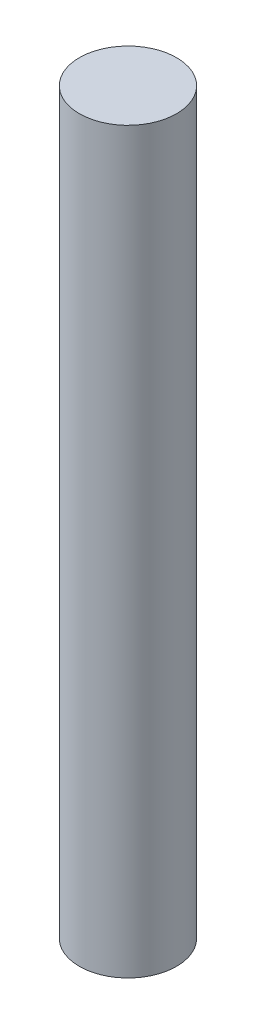
SolidWorks part; units mm, degrees
ref_plane "Front" through (0, 0, 0) normal (0, 0, 1) x (1, 0, 0)
ref_plane "Top" through (0, 0, 0) normal (0, 1, 0) x (1, 0, 0)
ref_plane "Right" through (0, 0, 0) normal (1, 0, 0) x (0, 0, -1)
sketch "Çizim1" plane through (0, 0, 0) normal (0, 1, 0) x (1, 0, 0)
  circle A0 centre (0, 0) radius 2.5
  dimension "D1" = 5
extrude "Yükseklik-Ekstrüzyon1" add sketch "Çizim1" along normal blind 38
